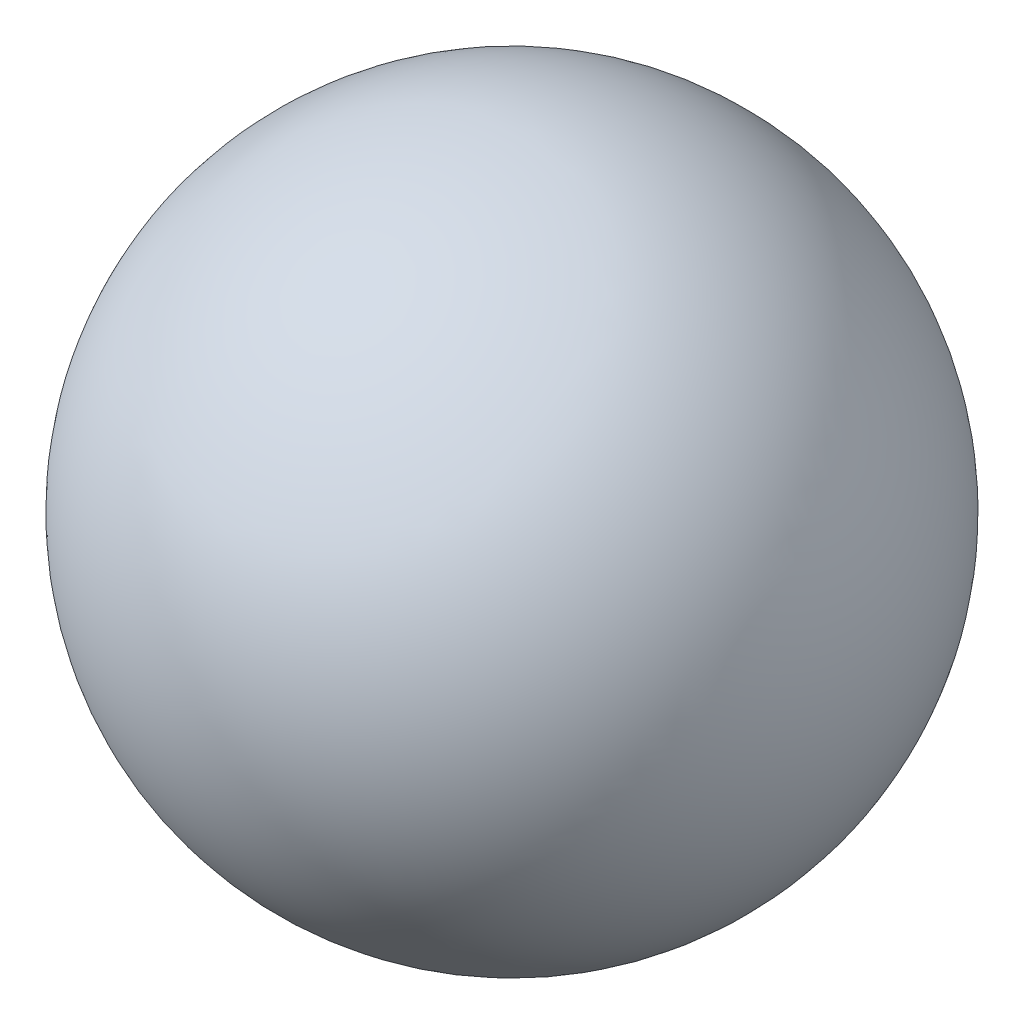
SolidWorks part; units mm, degrees
ref_plane "Front Plane" through (0, 0, 0) normal (0, 0, 1) x (1, 0, 0)
ref_plane "Top Plane" through (0, 0, 0) normal (0, 1, 0) x (1, 0, 0)
ref_plane "Right Plane" through (0, 0, 0) normal (1, 0, 0) x (0, 0, -1)
sketch "Sketch1" plane through (0, 0, 0) normal (0, 0, 1) x (1, 0, 0)
  line L0 (-4, 0) -> (4, 0)
  arc A0 (4, 0) -> (-4, 0) centre (0, 0) cw
  dimension "D1" = 8
revolve "Revolve1" add sketch "Sketch1" angle 360 about L0
